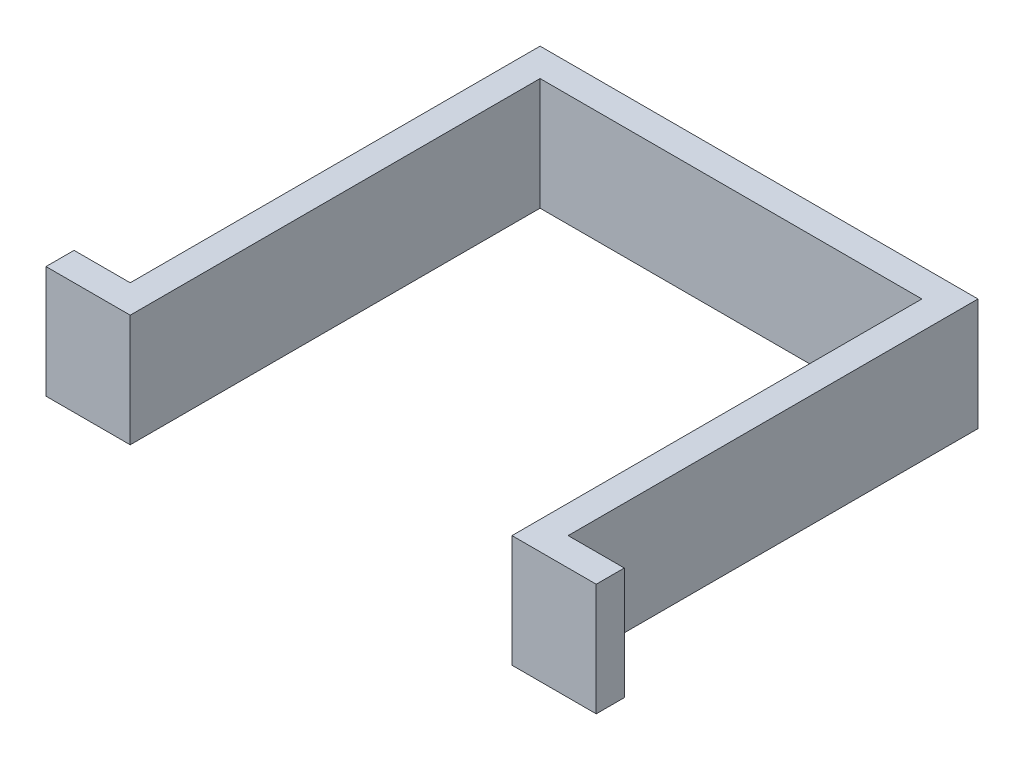
SolidWorks part; units mm, degrees
ref_plane "Front Plane" through (0, 0, 0) normal (0, 0, 1) x (1, 0, 0)
ref_plane "Top Plane" through (0, 0, 0) normal (0, 1, 0) x (1, 0, 0)
ref_plane "Right Plane" through (0, 0, 0) normal (1, 0, 0) x (0, 0, -1)
sketch "Sketch1" plane through (0, 0, 0) normal (0, 1, 0) x (1, 0, 0)
  line L0 (-49.4643, 0) -> (-34.4643, 0)
  line L1 (-34.4643, 0) -> (-34.4643, 73)
  line L2 (-34.4643, 73) -> (33.5357, 73)
  line L3 (33.5357, 73) -> (33.5357, 0)
  line L4 (33.5357, 0) -> (48.5357, 0)
  line L5 (48.5357, 0) -> (48.5357, 5)
  line L6 (48.5357, 5) -> (38.5357, 5)
  line L7 (38.5357, 5) -> (38.5357, 78)
  line L8 (38.5357, 78) -> (-39.4643, 78)
  line L9 (-39.4643, 78) -> (-39.4643, 5)
  line L10 (-39.4643, 5) -> (-49.4643, 5)
  line L11 (-49.4643, 5) -> (-49.4643, 0)
  dimension "D1" = 78
  dimension "D2" = 68
  dimension "D3" = 5
  dimension "D4" = 5
  dimension "D5" = 10
  dimension "D6" = 10
  dimension "D7" = 5
  dimension "D8" = 5
  dimension "D9" = 73
  dimension "D10" = 73
  dimension "D11" = 73
extrude "Boss-Extrude1" add sketch "Sketch1" along normal blind 20
